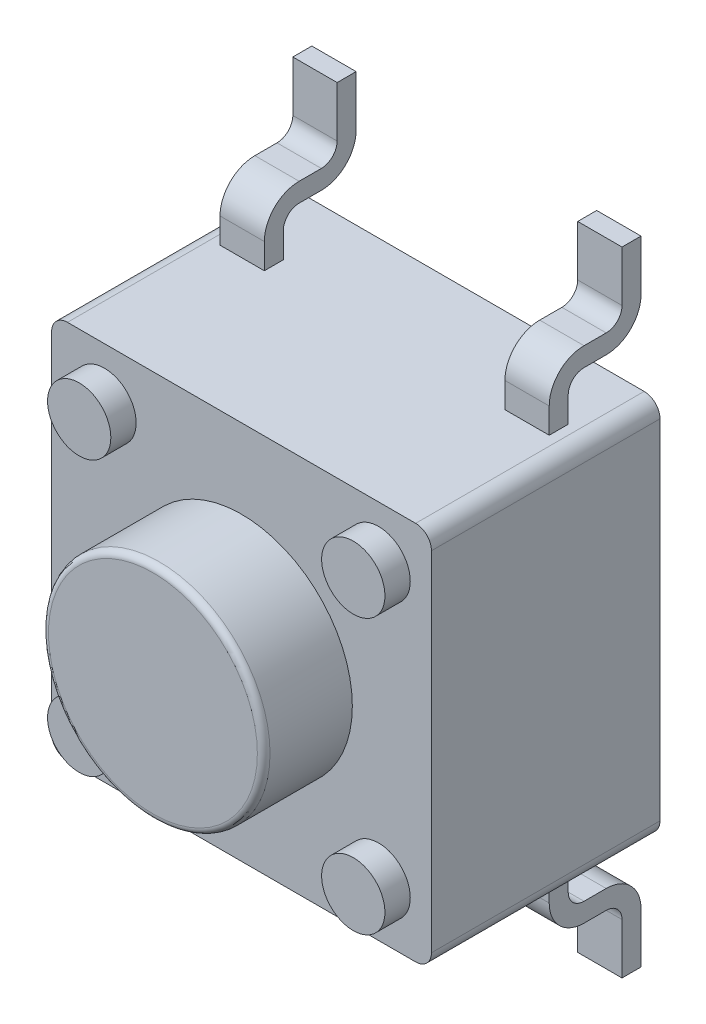
SolidWorks part; units mm, degrees
ref_plane "Front Plane" through (0, 0, 0) normal (0, 0, 1) x (1, 0, 0)
ref_plane "Top Plane" through (0, 0, 0) normal (0, 1, 0) x (1, 0, 0)
ref_plane "Right Plane" through (0, 0, 0) normal (1, 0, 0) x (0, 0, -1)
sketch "Sketch1" plane through (0, 0, 0) normal (0, 0, 1) x (1, 0, 0)
  line L0 (3, -3) -> (3, 3)
  line L1 (3, 3) -> (-3, 3)
  line L2 (-3, 3) -> (-3, -3)
  line L3 (-3, -3) -> (3, -3)
extrude "Boss-Extrude1" add sketch "Sketch1" against normal blind 3.61
sketch "Sketch2" plane through (0, -3, 0) normal (0, -1, 0) x (1, 0, 0)
  line L0 (-2.6, -2.26) -> (-1.9, -2.26)
  line L1 (-1.9, -2.26) -> (-1.9, -2.56)
  line L2 (-1.9, -2.56) -> (-2.6, -2.56)
  line L3 (-2.6, -2.56) -> (-2.6, -2.26)
extrude "Boss-Extrude2" add sketch "Sketch2" along normal blind 2
sketch "Sketch3" plane through (0, 0, -2.56) normal (0, 0, -1) x (-1, 0, 0)
  line L0 (2.6, -5) -> (1.9, -5)
  line L1 (1.9, -5) -> (1.9, -3.65)
  line L2 (1.9, -3.65) -> (2.6, -3.65)
  line L3 (2.6, -3.65) -> (2.6, -5)
extrude "Boss-Extrude3" add sketch "Sketch3" along normal blind 1.15
sketch "Sketch4" plane through (0, -3, 0) normal (0, -1, 0) x (1, 0, 0)
  line L0 (1.9, -2.26) -> (2.6, -2.26)
  line L1 (2.6, -2.26) -> (2.6, -2.56)
  line L2 (2.6, -2.56) -> (1.9, -2.56)
  line L3 (1.9, -2.56) -> (1.9, -2.26)
extrude "Boss-Extrude4" add sketch "Sketch4" along normal blind 2
sketch "Sketch5" plane through (0, 0, -2.56) normal (0, 0, -1) x (-1, 0, 0)
  line L0 (-1.9, -5) -> (-2.6, -5)
  line L1 (-2.6, -5) -> (-2.6, -3.65)
  line L2 (-2.6, -3.65) -> (-1.9, -3.65)
  line L3 (-1.9, -3.65) -> (-1.9, -5)
extrude "Boss-Extrude5" add sketch "Sketch5" along normal blind 1.15
sketch "Sketch6" plane through (0, 3, 0) normal (0, 1, 0) x (-1, 0, 0)
  line L0 (1.9, -2.26) -> (2.6, -2.26)
  line L1 (2.6, -2.26) -> (2.6, -2.56)
  line L2 (2.6, -2.56) -> (1.9, -2.56)
  line L3 (1.9, -2.56) -> (1.9, -2.26)
extrude "Boss-Extrude6" add sketch "Sketch6" along normal blind 2
sketch "Sketch7" plane through (0, 0, -2.56) normal (0, 0, -1) x (-1, 0, 0)
  line L0 (1.9, 3.65) -> (1.9, 5)
  line L1 (1.9, 5) -> (2.6, 5)
  line L2 (2.6, 5) -> (2.6, 3.65)
  line L3 (2.6, 3.65) -> (1.9, 3.65)
extrude "Boss-Extrude7" add sketch "Sketch7" along normal blind 1.15
sketch "Sketch8" plane through (0, 3, 0) normal (0, 1, 0) x (-1, 0, 0)
  line L0 (-2.6, -2.26) -> (-1.9, -2.26)
  line L1 (-1.9, -2.26) -> (-1.9, -2.56)
  line L2 (-1.9, -2.56) -> (-2.6, -2.56)
  line L3 (-2.6, -2.56) -> (-2.6, -2.26)
extrude "Boss-Extrude8" add sketch "Sketch8" along normal blind 2
sketch "Sketch9" plane through (0, 0, -2.56) normal (0, 0, -1) x (-1, 0, 0)
  line L0 (-2.6, 3.65) -> (-2.6, 5)
  line L1 (-2.6, 5) -> (-1.9, 5)
  line L2 (-1.9, 5) -> (-1.9, 3.65)
  line L3 (-1.9, 3.65) -> (-2.6, 3.65)
extrude "Boss-Extrude9" add sketch "Sketch9" along normal blind 1.15
sketch "Sketch10" plane through (-2.6, 0, 0) normal (-1, 0, 0) x (0, 0, 1)
  line L0 (-2.26, -5) -> (-2.26, -3.95)
  line L1 (-2.26, -3.95) -> (-3.41, -3.95)
  line L2 (-3.41, -3.95) -> (-3.41, -5)
  line L3 (-3.41, -5) -> (-2.26, -5)
extrude "Cut-Extrude1" cut sketch "Sketch10" against normal up to next
sketch "Sketch11" plane through (1.9, 0, 0) normal (-1, 0, 0) x (0, 0, 1)
  line L0 (-2.26, -5) -> (-2.26, -3.95)
  line L1 (-2.26, -3.95) -> (-3.41, -3.95)
  line L2 (-3.41, -3.95) -> (-3.41, -5)
  line L3 (-3.41, -5) -> (-2.26, -5)
extrude "Cut-Extrude2" cut sketch "Sketch11" against normal through all
sketch "Sketch12" plane through (-2.6, 0, 0) normal (-1, 0, 0) x (0, 0, 1)
  line L0 (-2.26, 5) -> (-3.41, 5)
  line L1 (-3.41, 5) -> (-3.41, 3.95)
  line L2 (-3.41, 3.95) -> (-2.26, 3.95)
  line L3 (-2.26, 3.95) -> (-2.26, 5)
extrude "Cut-Extrude3" cut sketch "Sketch12" against normal up to next
sketch "Sketch13" plane through (1.9, 0, 0) normal (-1, 0, 0) x (0, 0, 1)
  line L0 (-2.26, 5) -> (-3.41, 5)
  line L1 (-3.41, 5) -> (-3.41, 3.95)
  line L2 (-3.41, 3.95) -> (-2.26, 3.95)
  line L3 (-2.26, 3.95) -> (-2.26, 5)
extrude "Cut-Extrude4" cut sketch "Sketch13" against normal through all
ref_plane "Plane1" through (0, -2.165, 0) normal (0, 1, 0) x (-1, 0, 0)
sketch "Sketch14" plane through (0, -2.165, 0) normal (0, 1, 0) x (-1, 0, 0)
  line L0 (-2.665, 0) -> (-2.165, 0)
  line L1 (-2.165, 0) -> (-2.165, 0.4)
  line L2 (-2.165, 0.4) -> (-2.665, 0.4)
  line L3 (-2.665, 0.4) -> (-2.665, 0)
  line L4 (-2.165, 0) -> (-2.165, 0.4) construction
revolve "Revolve1" add sketch "Sketch14" angle 360 about L4
sketch "Sketch15" plane through (0, -2.165, 0) normal (0, 1, 0) x (-1, 0, 0)
  line L0 (1.665, 0) -> (2.165, 0)
  line L1 (2.165, 0) -> (2.165, 0.4)
  line L2 (2.165, 0.4) -> (1.665, 0.4)
  line L3 (1.665, 0.4) -> (1.665, 0)
  line L4 (2.165, 0) -> (2.165, 0.4) construction
revolve "Revolve2" add sketch "Sketch15" angle 360 about L4
ref_plane "Plane2" through (0, 2.165, 0) normal (0, 1, 0) x (-1, 0, 0)
sketch "Sketch16" plane through (0, 2.165, 0) normal (0, 1, 0) x (-1, 0, 0)
  line L0 (1.665, 0) -> (2.165, 0)
  line L1 (2.165, 0) -> (2.165, 0.4)
  line L2 (2.165, 0.4) -> (1.665, 0.4)
  line L3 (1.665, 0.4) -> (1.665, 0)
  line L4 (2.165, 0) -> (2.165, 0.4) construction
revolve "Revolve3" add sketch "Sketch16" angle 360 about L4
sketch "Sketch17" plane through (0, 2.165, 0) normal (0, 1, 0) x (-1, 0, 0)
  line L0 (-2.665, 0) -> (-2.165, 0)
  line L1 (-2.165, 0) -> (-2.165, 0.4)
  line L2 (-2.165, 0.4) -> (-2.665, 0.4)
  line L3 (-2.665, 0.4) -> (-2.665, 0)
  line L4 (-2.165, 0) -> (-2.165, 0.4) construction
revolve "Revolve4" add sketch "Sketch17" angle 360 about L4
fillet "Fillet1" radius 0.25 12 edges at (2.25, -3.65, -2.56) (3, 3, -1.805) (-3, -3, -1.805) (-2.25, -3.95, -3.41) (2.25, 3.95, -3.41) (-2.25, 3.95, -3.41) (3, -3, -1.805) (2.25, -3.95, -3.41) (-3, 3, -1.805) (2.25, 3.65, -2.56) (-2.25, 3.65, -2.56) (-2.25, -3.65, -2.56)
fillet "Fillet2" radius 0.55 8 edges at (2.25, 3.95, -2.26) (-2.25, 3.95, -2.26) (-2.25, -3.95, -2.26) (-2.25, -3.65, -3.71) (2.25, 3.65, -3.71) (2.25, -3.95, -2.26) (2.25, -3.65, -3.71) (-2.25, 3.65, -3.71)
sketch "Sketch19" plane through (0, 0, 0) normal (0, 0, 1) x (1, 0, 0)
  circle A0 centre (0, 0) radius 1.75
extrude "Boss-Extrude10" add sketch "Sketch19" along normal blind 1.4
fillet "Fillet4" radius 0.1 1 edges at (1.75, 0, 1.4)
